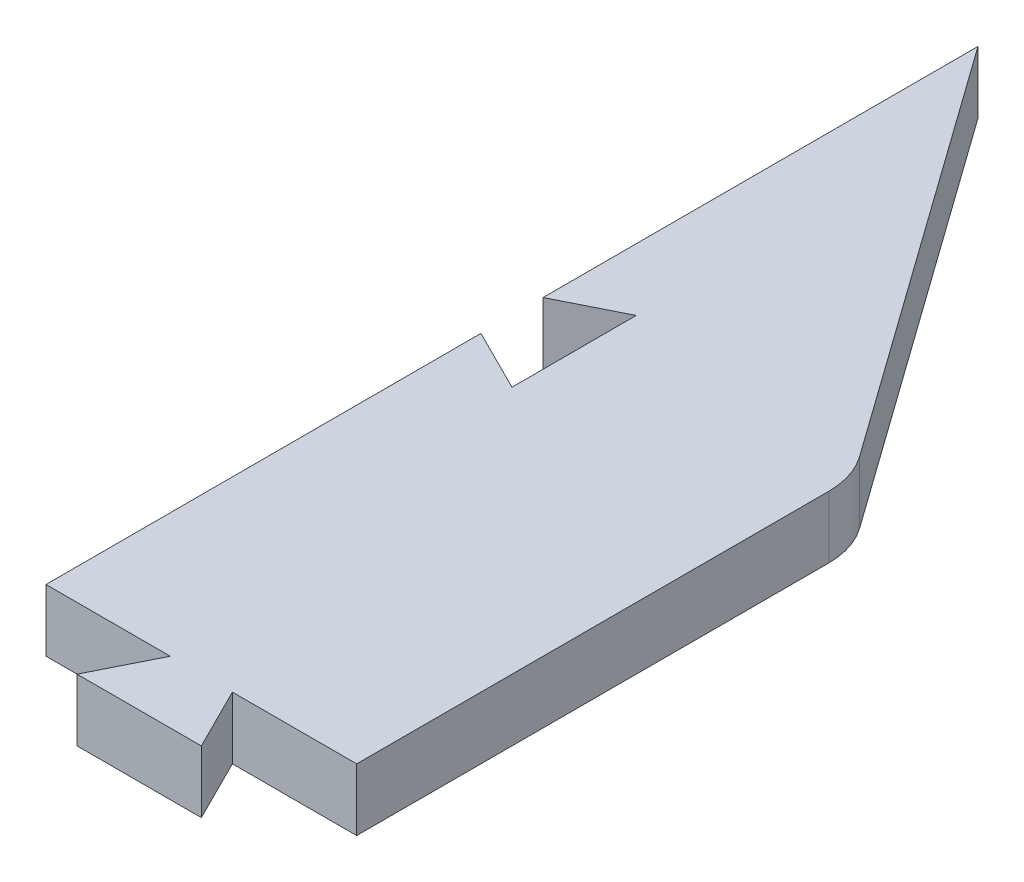
SolidWorks part; units mm, degrees
ref_plane "Спереди" through (0, 0, 0) normal (0, 0, 1) x (1, 0, 0)
ref_plane "Сверху" through (0, 0, 0) normal (0, 1, 0) x (1, 0, 0)
ref_plane "Справа" through (0, 0, 0) normal (1, 0, 0) x (0, 0, -1)
sketch "Эскиз1" plane through (0, 0, 0) normal (0, 1, 0) x (1, 0, 0)
  line L0 (29.0687, 15.8039) -> (10, 42.5)
  line L1 (18, -17.5) -> (10, -17.5)
  line L2 (10, -17.5) -> (10, 10.5)
  line L3 (20, -12.2343) -> (20, 16.5) construction
  line L9 (14, 16.5) -> (10, 14.5)
  line L10 (14, 16.5) -> (14, 8.5)
  line L12 (10, -3.5) -> (10, 24.4799) construction
  line L13 (10, 42.5) -> (10, 52.0644) construction
  line L18 (14, 8.5) -> (10, 10.5)
  line L19 (22, -17.5) -> (30, -17.5)
  line L20 (10, 14.5) -> (10, 42.5)
  line L24 (24, -21.5) -> (22, -17.5)
  line L25 (16, -21.5) -> (18, -17.5)
  line L26 (24, -21.5) -> (16, -21.5)
  line L27 (30, -17.5) -> (30, 12.8977)
  arc A0 (30, 12.8977) -> (29.0687, 15.8039) centre (25, 12.8977) ccw
  dimension "D1" = 5
  dimension "D3" = 60
extrude "Бобышка-Вытянуть1" add sketch "Эскиз1" along normal blind 4 contours L20 L0 A0 L27 L19 L24 L26 L25 L1 L2 L18 L10 L9
